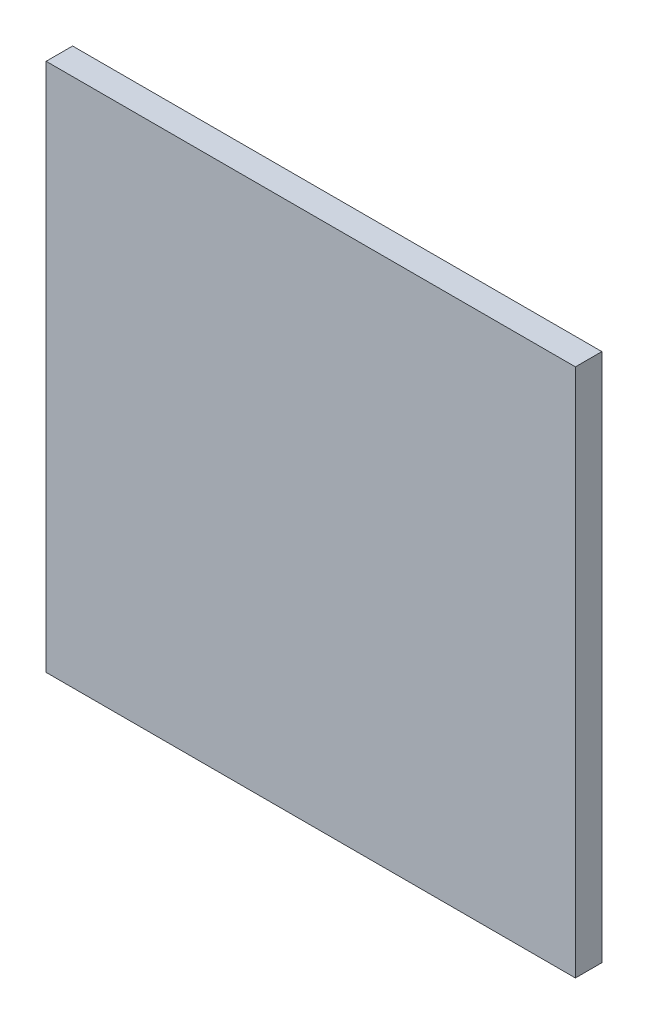
SolidWorks part; units mm, degrees
ref_plane "Plan de face" through (0, 0, 0) normal (0, 0, 1) x (1, 0, 0)
ref_plane "Plan de dessus" through (0, 0, 0) normal (0, 1, 0) x (1, 0, 0)
ref_plane "Plan de droite" through (0, 0, 0) normal (1, 0, 0) x (0, 0, -1)
sketch "Esquisse1" plane through (0, 0, 0) normal (0, 0, 1) x (1, 0, 0)
  line L1 (-2, 2) -> (2, 2)
  line L2 (-2, 2) -> (-2, -2)
  line L3 (-2, -2) -> (2, -2)
  line L4 (2, 2) -> (2, -2)
  dimension "D1" = 4
  dimension "D2" = 2
  dimension "D3" = 4
  dimension "D4" = 2
extrude "Boss.-Extru.1" add sketch "Esquisse1" along normal blind 0.2
